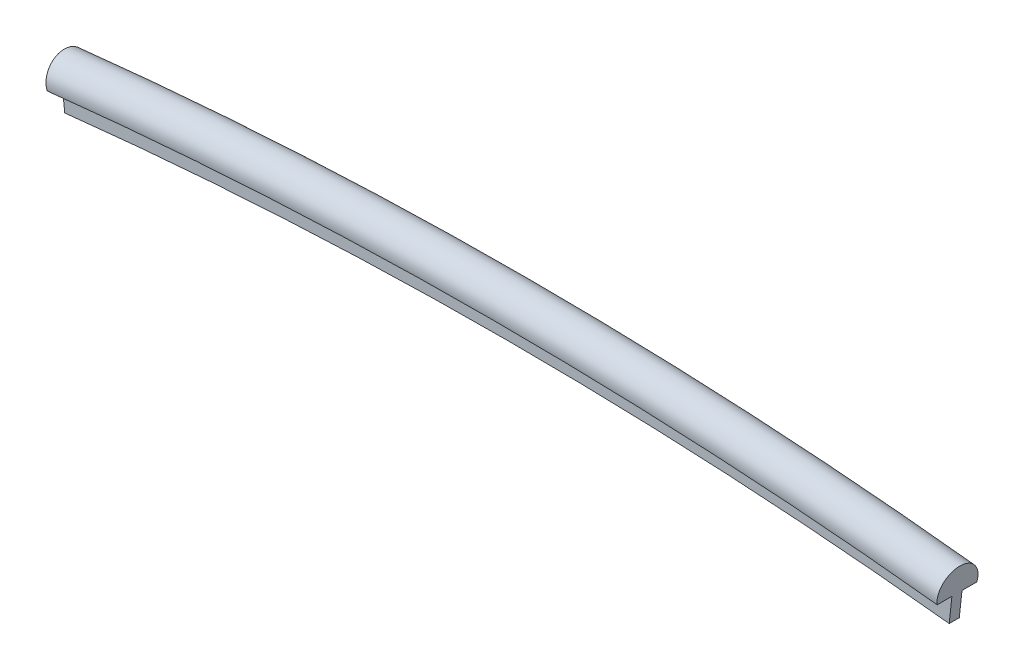
SolidWorks part; units mm, degrees
ref_plane "Front Plane" through (0, 0, 0) normal (0, 0, 1) x (1, 0, 0)
ref_plane "Top Plane" through (0, 0, 0) normal (0, 1, 0) x (1, 0, 0)
ref_plane "Right Plane" through (0, 0, 0) normal (1, 0, 0) x (0, 0, -1)
sketch "Sketch2" plane through (0, 0, 0) normal (1, 0, 0) x (0, 0, -1)
  line L0 (0, 241.3) -> (0, 0) construction
  line L2 (0, 241.3) -> (0, 239.8) construction
  line L3 (0, 239.8) -> (0.3, 239.8)
  line L4 (0, 239.8) -> (-0.3, 239.8)
  line L5 (-0.3, 239.8) -> (-0.3, 241.3)
  line L6 (0.3, 239.8) -> (0.3, 241.3)
  line L7 (0, 241.3) -> (0, 242.8) construction
  line L8 (-1.18, 241.3) -> (-0.3, 241.3)
  line L9 (0.3, 241.3) -> (1.18, 241.3)
  arc A0 (-1.18, 241.3) -> (1.18, 241.3) centre (0, 241.586) cw
  point P14 (0, 241.3)
ref_axis "Axis2" through (0, 0, 70.5976) along (0, 0, -1)
revolve "Revolve1" add sketch "Sketch2" angle 6.309 about axis through (0, 0, 70.5976) along (0, 0, -1)
